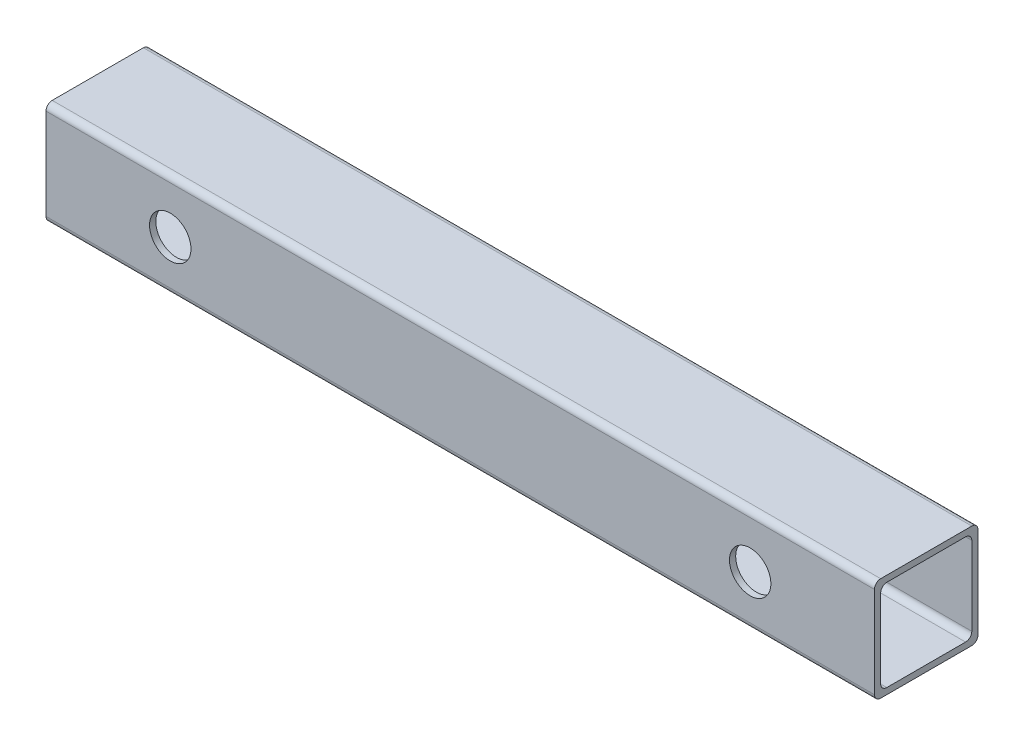
SolidWorks part; units mm, degrees
ref_plane "Front Plane" through (0, 0, 0) normal (0, 0, 1) x (1, 0, 0)
ref_plane "Top Plane" through (0, 0, 0) normal (0, 1, 0) x (1, 0, 0)
ref_plane "Right Plane" through (0, 0, 0) normal (1, 0, 0) x (0, 0, -1)
sketch "Sketch1" plane through (0, 0, 0) normal (1, 0, 0) x (0, 0, -1)
  line L1 (1.5, 0) -> (23.5, 0)
  line L2 (0, 1.5) -> (0, 23.5)
  line L3 (1.5, 25) -> (23.5, 25)
  line L4 (25, 1.5) -> (25, 23.5)
  line L5 (3, 23.5) -> (22, 23.5)
  line L6 (1.5, 22) -> (1.5, 3)
  line L7 (3, 1.5) -> (22, 1.5)
  line L8 (23.5, 22) -> (23.5, 3)
  arc A0 (23.5, 25) -> (25, 23.5) centre (23.5, 23.5) cw
  arc A1 (22, 23.5) -> (23.5, 22) centre (22, 22) cw
  arc A2 (23.5, 0) -> (25, 1.5) centre (23.5, 1.5) ccw
  arc A3 (22, 1.5) -> (23.5, 3) centre (22, 3) ccw
  arc A4 (1.5, 3) -> (3, 1.5) centre (3, 3) ccw
  arc A5 (1.5, 0) -> (0, 1.5) centre (1.5, 1.5) cw
  arc A6 (1.5, 22) -> (3, 23.5) centre (3, 22) cw
  arc A7 (0, 23.5) -> (1.5, 25) centre (1.5, 23.5) cw
  point P13 (23.5, 23.5)
  point P16 (25, 0)
  point P21 (1.5, 1.5)
  point P24 (0, 0)
  point P27 (1.5, 23.5)
  point P30 (0, 25)
  dimension "D6" = 1.5
  dimension "D1" = 25
  dimension "D2" = 25
  dimension "D3" = 22
  dimension "22" = 22
  dimension "D4" = 1.5
  dimension "D5" = 1.5
extrude "Boss-Extrude1" add sketch "Sketch1" along normal blind 200
sketch "Sketch3" plane through (0, 0, -25) normal (0, 0, -1) x (-1, 0, 0)
  line L0 (-200, 1.5) -> (-200, 23.5) construction
  circle A0 centre (-170, 12.1767) radius 5
  circle A1 centre (-30, 12.1767) radius 5
  dimension "D1" = 10
  dimension "D4" = 140
  dimension "D2" = 30
  dimension "D3" = 2
extrude "Cut-Extrude1" cut sketch "Sketch3" against normal through all
